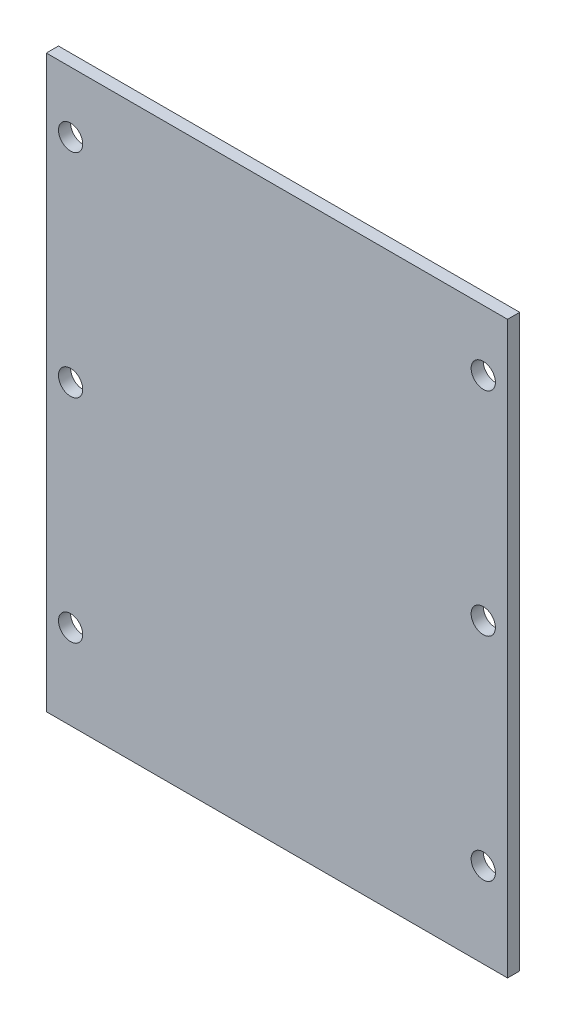
SolidWorks part; units mm, degrees
ref_plane "Płaszczyzna przednia" through (0, 0, 0) normal (0, 0, 1) x (1, 0, 0)
ref_plane "Płaszczyzna górna" through (0, 0, 0) normal (0, 1, 0) x (1, 0, 0)
ref_plane "Płaszczyzna prawa" through (0, 0, 0) normal (1, 0, 0) x (0, 0, -1)
sketch "Szkic1" plane through (0, 0, 0) normal (0, 0, 1) x (1, 0, 0)
  line L1 (38, 47) -> (-38, 47)
  line L2 (38, 47) -> (38, -47)
  line L3 (38, -47) -> (-38, -47)
  line L4 (-38, 47) -> (-38, -47)
  line L5 (38, 47) -> (-38, -47) construction
  line L6 (38, -47) -> (-38, 47) construction
  point P0 (0, 0)
  dimension "D1" = 76
  dimension "D2" = 94
extrude "Dodanie-wyciągnięcie1" add sketch "Szkic1" along normal blind 2
sketch "Szkic2" plane through (0, 0, 2) normal (0, 0, 1) x (1, 0, 0)
  circle A6 centre (34, 37) radius 2
  circle A7 centre (34, 2) radius 2
  circle A8 centre (34, -33) radius 2
  circle A9 centre (-34, -33) radius 2
  circle A10 centre (-34, 2) radius 2
  circle A11 centre (-34, 37) radius 2
extrude "Wytnij-wyciągnięcie1" cut sketch "Szkic2" against normal blind 2
